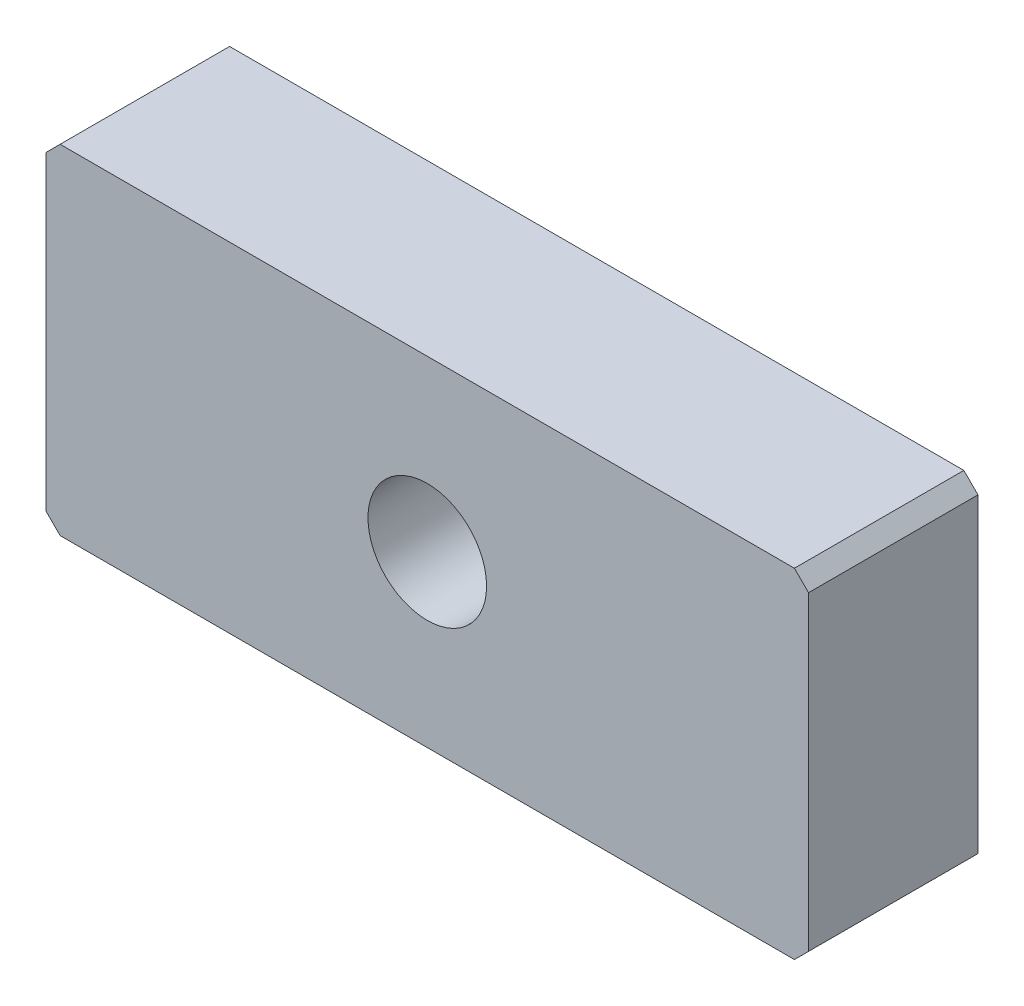
SolidWorks part; units mm, degrees
material "Balsa"
ref_plane "Front Plane" through (0, 0, 0) normal (0, 0, 1) x (1, 0, 0)
ref_plane "Top Plane" through (0, 0, 0) normal (0, 1, 0) x (1, 0, 0)
ref_plane "Right Plane" through (0, 0, 0) normal (1, 0, 0) x (0, 0, -1)
sketch "Sketch1" plane through (0, 0, 0) normal (0, 0, 1) x (1, 0, 0)
  line L0 (13.5, 0) -> (13.5, 12) construction
  line L1 (0, 0) -> (27, 0)
  line L2 (0, 0) -> (0, 12)
  line L3 (0, 12) -> (27, 12)
  line L4 (27, 0) -> (27, 12)
  line L5 (0, 6) -> (27, 6) construction
  circle A0 centre (13.5, 6) radius 2.1
  dimension "D3" = 4.2
  dimension "D1" = 12
  dimension "D2" = 27
extrude "Boss-Extrude1" add sketch "Sketch1" along normal blind 6
chamfer "Chamfer1" distance 0.5 angle 45 4 edges at (0, 0, 3) (0, 12, 3) (27, 12, 3) (27, 0, 3)
